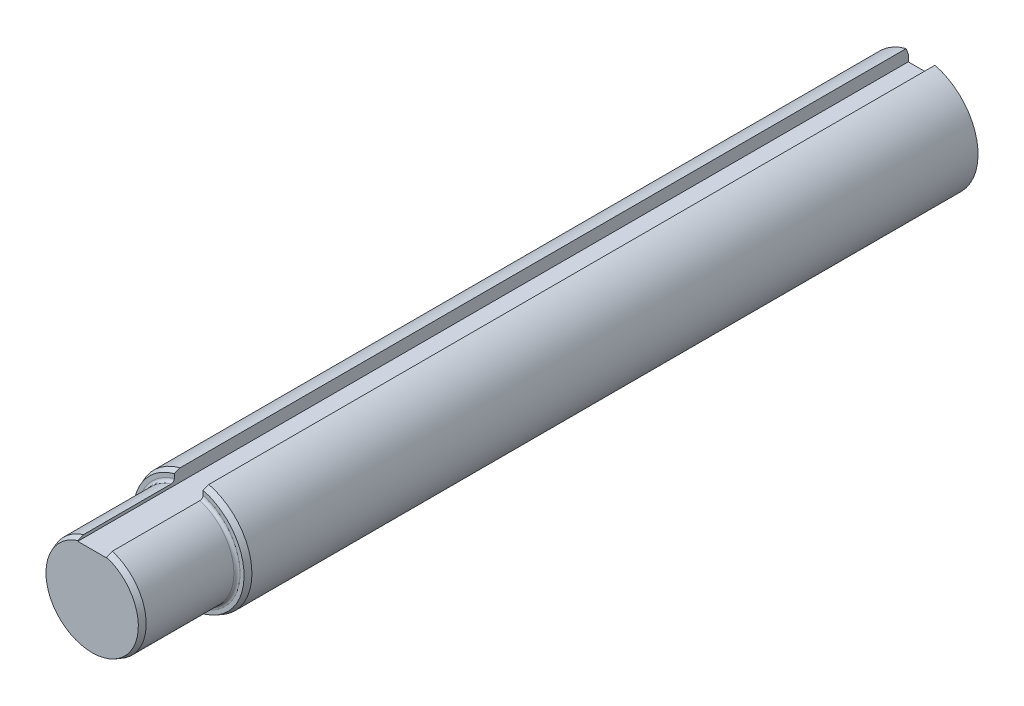
SolidWorks part; units mm, degrees
ref_plane "Front Plane" through (0, 0, 0) normal (0, 0, 1) x (1, 0, 0)
ref_plane "Top Plane" through (0, 0, 0) normal (0, 1, 0) x (1, 0, 0)
ref_plane "Right Plane" through (0, 0, 0) normal (1, 0, 0) x (0, 0, -1)
sketch "Sketch1" plane through (0, 0, 0) normal (0, 0, 1) x (1, 0, 0)
  line L1 (-1.1938, 3.5719) -> (1.1938, 3.5719)
  line L2 (-1.1938, 3.5719) -> (-1.1938, 4.7625)
  line L3 (-1.1938, 4.7625) -> (1.1938, 4.7625)
  line L4 (1.1938, 3.5719) -> (1.1938, 4.7625)
  line L5 (-1.1938, 3.5719) -> (1.1938, 4.7625) construction
  line L6 (-1.1938, 4.7625) -> (1.1938, 3.5719) construction
  circle A0 centre (0, 0) radius 4.7625
  point P3 (0, 4.1672)
  dimension "Diameter" = 9.525
  dimension "Keyway Width" = 2.3876
  dimension "Keyway Depth" = 1.1906
sketch "Sketch2" plane through (0, 0, 0) normal (1, 0, 0) x (0, 0, -1)
  line L0 (0, 4.7625) -> (0, -4.7625) construction
  line L2 (76.2, -4.7625) -> (-76.2, -4.7625)
  line L3 (76.2, -4.7625) -> (76.2, 4.7625)
  line L4 (76.2, 4.7625) -> (-76.2, 4.7625)
  line L5 (-76.2, -4.7625) -> (-76.2, 4.7625)
  line L6 (76.2, -4.7625) -> (-76.2, 4.7625) construction
  line L7 (76.2, 4.7625) -> (-76.2, -4.7625) construction
  line L8 (-76.2, -4.7625) -> (76.2, -4.7625)
  point P0 (0, 0)
  point P3 (0, 0)
  point P9 (-61.9125, -4.7625)
  point P11 (61.9125, -4.7625)
  point P15 (0, -4.7625)
  dimension "Length" = 152.4
  dimension "Keyway Length" = 152.4
  dimension "D1" = 14.2875
  dimension "D2" = 14.2875
sketch "Sketch3" plane through (0, 0, 0) normal (0, 0, 1) x (1, 0, 0)
  line L1 (-1.1938, 4.7625) -> (1.1938, 4.7625)
  line L2 (-1.1938, 4.7625) -> (-1.1938, 3.5719)
  line L3 (-1.1938, 3.5719) -> (1.1938, 3.5719)
  line L4 (1.1938, 4.7625) -> (1.1938, 3.5719)
  circle A0 centre (0, 0) radius 4.7625 construction
  circle A1 centre (0, 0) radius 4.7625
extrude "Boss-Extrude1" add sketch "Sketch3" along normal blind 27.75 and the other way blind 41.0756 contours L2 A1 L4 L3
sketch "Sketch5" plane through (0, 0, 27.75) normal (0, 0, 1) x (1, 0, 0)
  circle A0 centre (0, 0) radius 4.7625
  circle A1 centre (0, 0) radius 4
extrude "Cut-Extrude1" cut sketch "Sketch5" against normal blind 8
chamfer "Chamfer1" distance 0.4763 angle 20 3 edges at (0, -4.7625, -41.0756) (0, -4.7625, 19.75) (0, -4, 27.75)
fillet "Fillet1" radius 0.254 1 edges at (0, -4, 19.75)
equation "\"D1@Chamfer1\"=\"Diameter@Sketch1\"*.05"
equation "\"D2@Sketch2\"=\"D1@Sketch2\""
equation "\"D1@Sketch2\"=\"Diameter@Sketch1\"*1.5"
